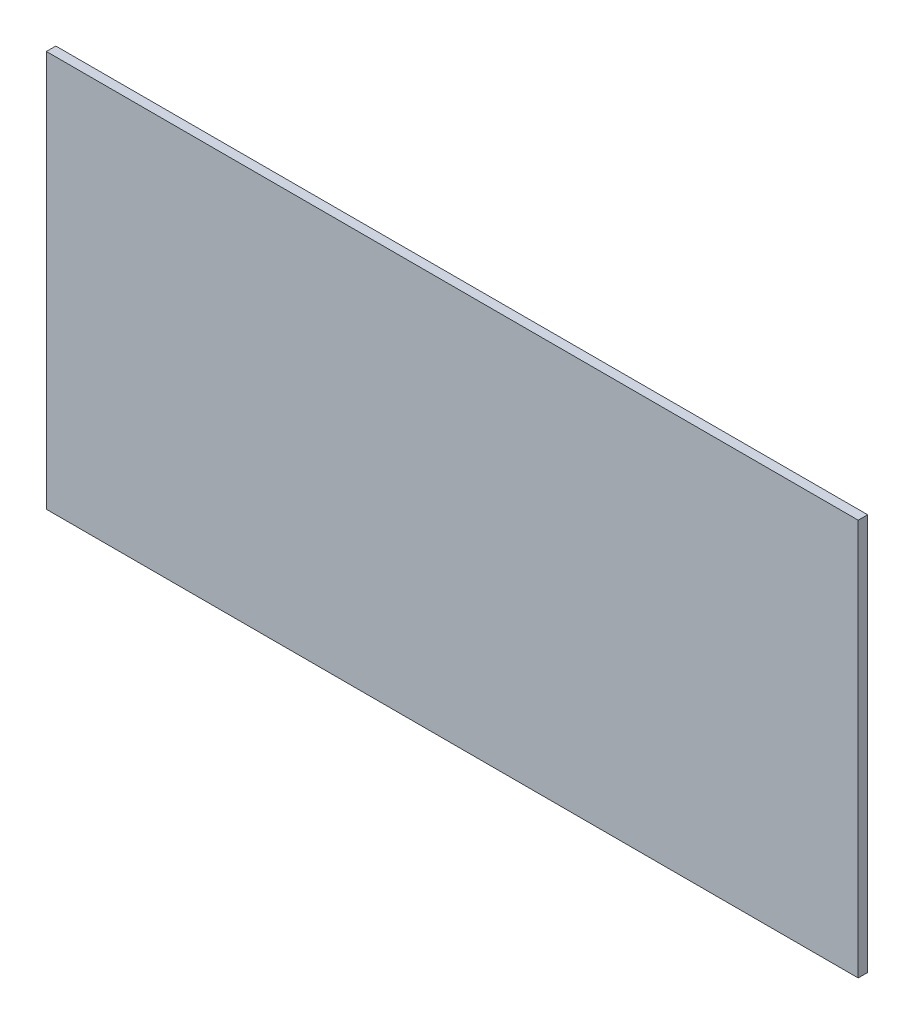
SolidWorks part; units mm, degrees
ref_plane "Front Plane" through (0, 0, 0) normal (0, 0, 1) x (1, 0, 0)
ref_plane "Top Plane" through (0, 0, 0) normal (0, 1, 0) x (1, 0, 0)
ref_plane "Right Plane" through (0, 0, 0) normal (1, 0, 0) x (0, 0, -1)
sketch "Sketch1" plane through (0, 0, 0) normal (0, 0, 1) x (1, 0, 0)
  line L1 (0, 0) -> (86, 0)
  line L2 (0, 0) -> (0, 42)
  line L3 (0, 42) -> (86, 42)
  line L4 (86, 0) -> (86, 42)
  dimension "D1" = 86
  dimension "D2" = 42
extrude "Profile" add sketch "Sketch1" along normal blind 1
equation "\"Profile_Depth\"= 1mm"
equation "\"D1@Profile\" = \"Profile_Depth\""
equation "\"Profile_Sketch_1\"= 86mm"
equation "\"D1@Sketch1\" = \"Profile_Sketch_1\""
equation "\"Profile_Sketch_2\"= 42mm"
equation "\"D2@Sketch1\" = \"Profile_Sketch_2\""
equation "\"EnvelopeWidth\"= 86mm"
equation "\"EnvelopeHeight\"= 42mm"
